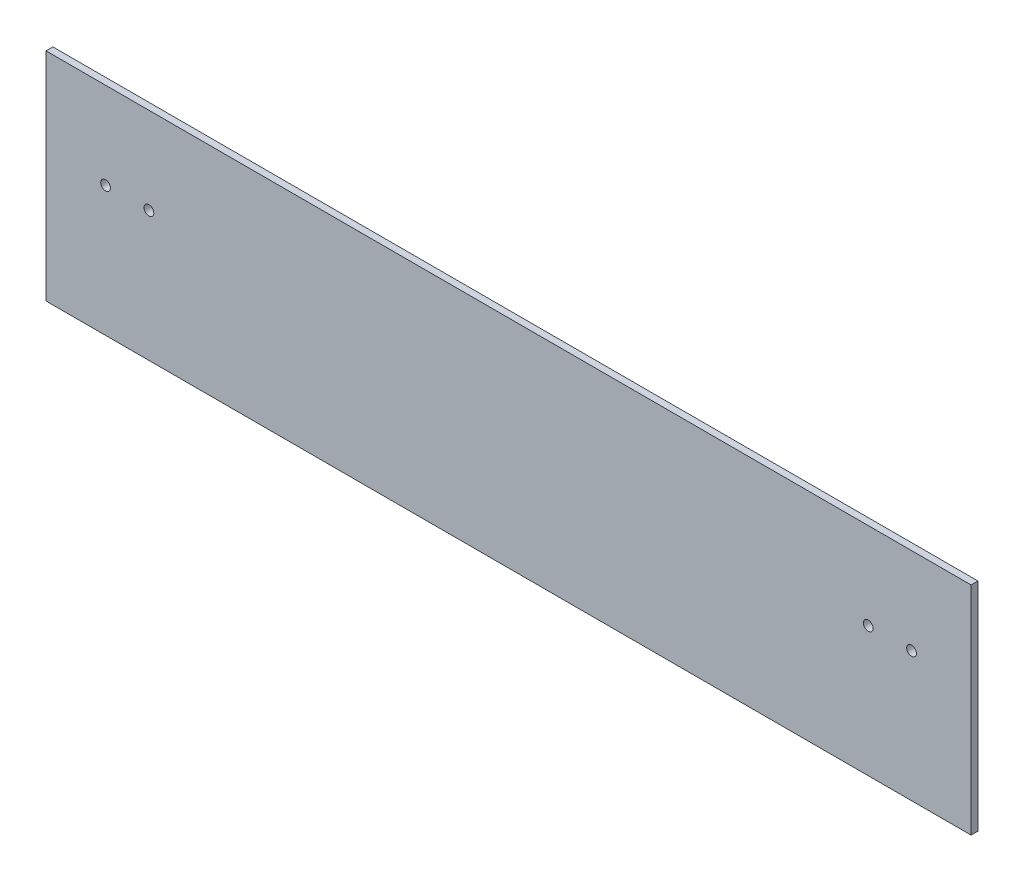
SolidWorks part; units mm, degrees
ref_plane "Front Plane" through (0, 0, 0) normal (0, 0, 1) x (1, 0, 0)
ref_plane "Top Plane" through (0, 0, 0) normal (0, 1, 0) x (1, 0, 0)
ref_plane "Right Plane" through (0, 0, 0) normal (1, 0, 0) x (0, 0, -1)
sketch "Sketch1" plane through (0, 0, 0) normal (0, 0, 1) x (1, 0, 0)
  line L1 (0, 0) -> (427, 0)
  line L2 (0, 0) -> (0, 100)
  line L3 (0, 100) -> (427, 100)
  line L4 (427, 0) -> (427, 100)
  dimension "D1" = 100
  dimension "D2" = 427
extrude "Boss-Extrude1" add sketch "Sketch1" along normal blind 3.175
sketch "Sketch2" plane through (0, 0, 0) normal (0, 0, -1) x (-1, 0, 0)
  line L1 (-427, 100) -> (0, 100) construction
  line L2 (-213.5, 100) -> (-213.5, 63.9603) construction
  circle A0 centre (-399.5, 60) radius 2.25
  circle A1 centre (-379.5, 60) radius 2.25
  circle A2 centre (-27.5, 60) radius 2.25
  circle A3 centre (-47.5, 60) radius 2.25
  dimension "D4" = 4.5
  dimension "D1" = 20
  dimension "D2" = 40
  dimension "D3" = 47.5
extrude "Cut-Extrude1" cut sketch "Sketch2" against normal through all
